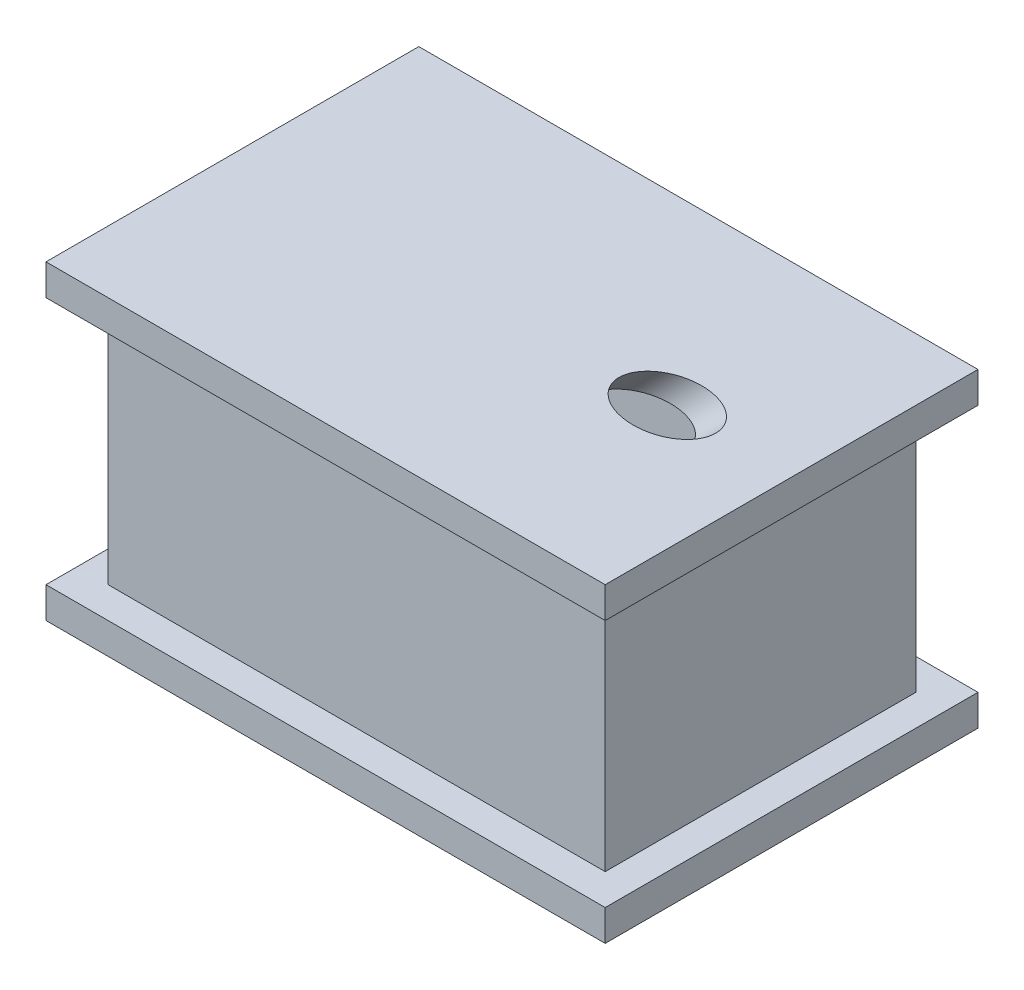
SolidWorks part; units mm, degrees
ref_plane "Front Plane" through (0, 0, 0) normal (0, 0, 1) x (1, 0, 0)
ref_plane "Top Plane" through (0, 0, 0) normal (0, 1, 0) x (1, 0, 0)
ref_plane "Right Plane" through (0, 0, 0) normal (1, 0, 0) x (0, 0, -1)
sketch "Sketch1" plane through (0, 0, 0) normal (0, 1, 0) x (1, 0, 0)
  line L0 (-2000, 1250) -> (-2000, -1250)
  line L1 (-1750, 1000) -> (1750, 1000)
  line L2 (-1750, 1000) -> (-1750, -1000)
  line L3 (-1750, -1000) -> (1750, -1000)
  line L4 (1750, 1000) -> (1750, -1000)
  line L5 (-1750, 1000) -> (1750, -1000) construction
  line L6 (-1750, -1000) -> (1750, 1000) construction
  line L7 (-2000, -1250) -> (2000, -1250)
  line L8 (2000, 1250) -> (2000, -1250)
  line L9 (-2000, 1250) -> (2000, 1250)
  point P0 (0, 0)
  dimension "D1" = 250
extrude "Boss-Extrude2" add sketch "Sketch1" along normal mid plane 2000
sketch "Sketch4" plane through (0, 1000, 0) normal (0, 1, 0) x (1, 0, 0)
  line L0 (2250, 1500) -> (-2250, 1500)
  line L1 (-2250, 1500) -> (-2250, -1500)
  line L2 (-2250, -1500) -> (2250, -1500)
  line L3 (2250, -1500) -> (2250, 1500)
extrude "Boss-Extrude3" add sketch "Sketch4" along normal blind 250
mirror "Mirror1" about plane through (0, 0, 0) normal (0, 1, 0) of "Boss-Extrude3"
ref_plane "Plane1" through (625, 625, 0) normal (0.7071, 0.7071, 0) x (0.7071, -0.7071, 0)
sketch "Sketch7" plane through (625, 625, 0) normal (0.7071, 0.7071, 0) x (0.7071, -0.7071, 0)
  circle A0 centre (0, 0) radius 275
  dimension "D1" = 550
extrude "Cut-Extrude1" cut sketch "Sketch7" along normal through all
